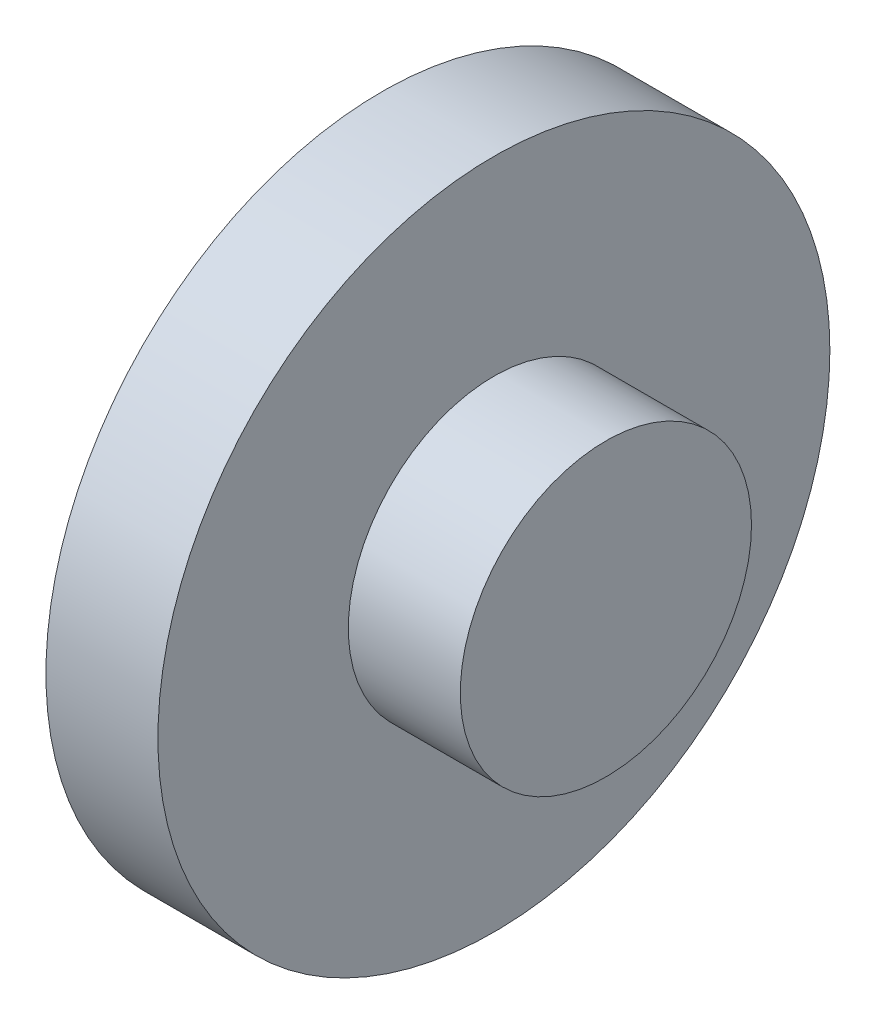
SolidWorks part; units mm, degrees
ref_plane "Front" through (0, 0, 0) normal (0, 0, 1) x (1, 0, 0)
ref_plane "Top" through (0, 0, 0) normal (0, 1, 0) x (1, 0, 0)
ref_plane "Right" through (0, 0, 0) normal (1, 0, 0) x (0, 0, -1)
sketch "草图1" plane through (0, 0, 0) normal (1, 0, 0) x (0, 0, -1)
  circle A0 centre (0, 0) radius 30
extrude "凸台-拉伸1" add sketch "草图1" along normal blind 10
sketch "草图2" plane through (10, 0, 0) normal (1, 0, 0) x (0, 0, -1)
  circle A0 centre (0, 0) radius 13
extrude "凸台-拉伸2" add sketch "草图2" along normal blind 10
